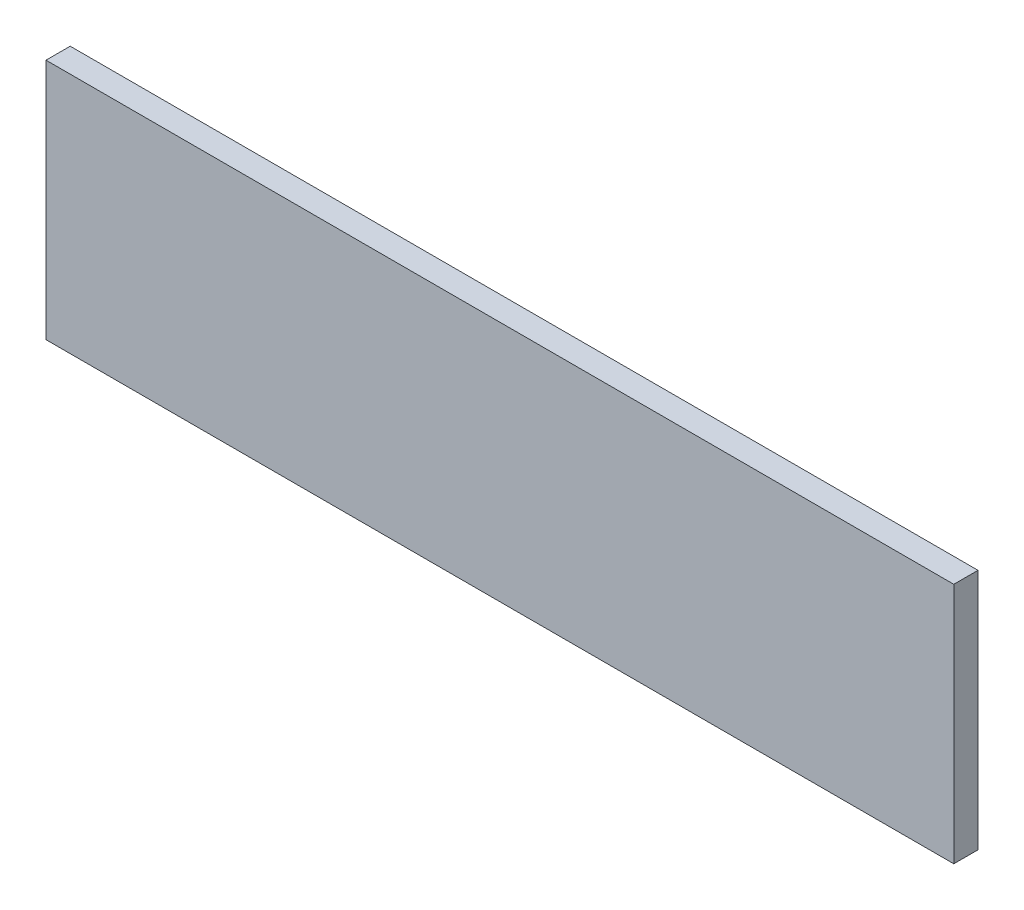
SolidWorks part; units mm, degrees
ref_plane "Front Plane" through (0, 0, 0) normal (0, 0, 1) x (1, 0, 0)
ref_plane "Top Plane" through (0, 0, 0) normal (0, 1, 0) x (1, 0, 0)
ref_plane "Right Plane" through (0, 0, 0) normal (1, 0, 0) x (0, 0, -1)
sketch "Sketch1" plane through (0, 0, 0) normal (0, 0, 1) x (1, 0, 0)
  line L1 (-94.1406, 21.747) -> (96.3594, 21.747)
  line L2 (-94.1406, 21.747) -> (-94.1406, -29.053)
  line L3 (-94.1406, -29.053) -> (96.3594, -29.053)
  line L4 (96.3594, 21.747) -> (96.3594, -29.053)
  dimension "D1" = 190.5
  dimension "D2" = 50.8
extrude "Boss-Extrude1" add sketch "Sketch1" along normal blind 5.08
